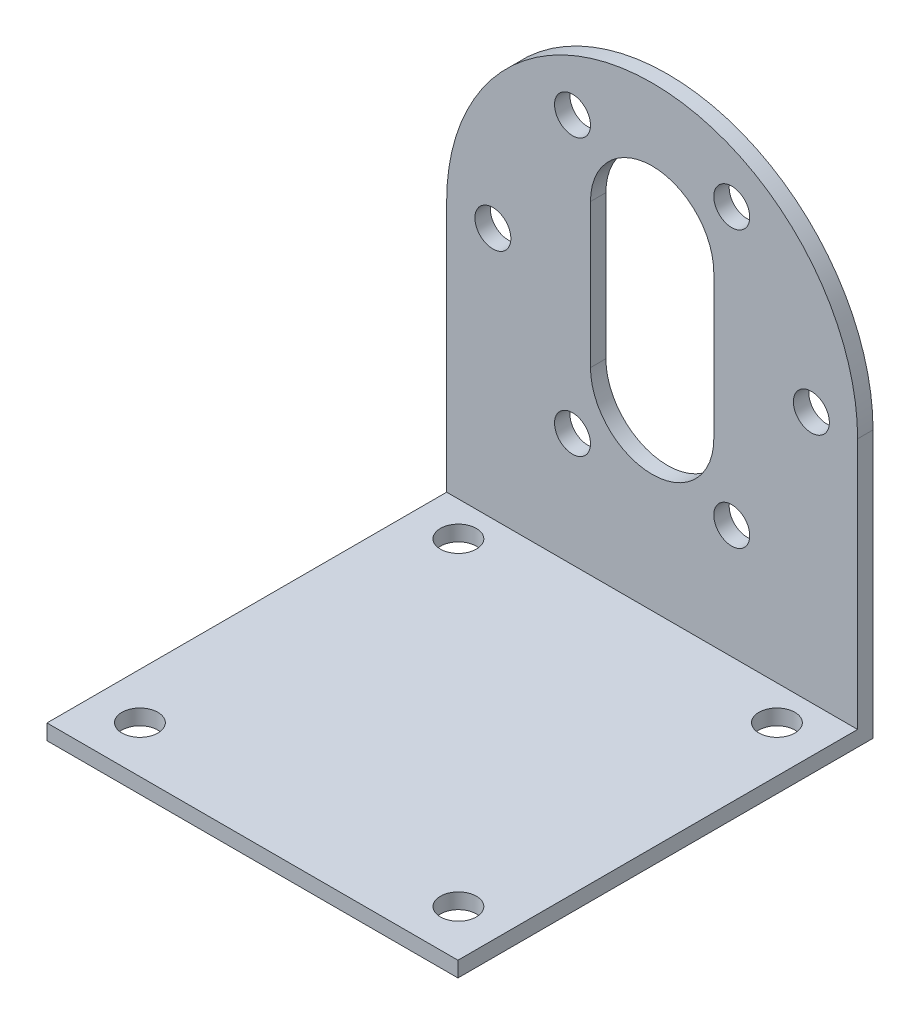
SolidWorks part; units mm, degrees
ref_plane "Front Plane" through (0, 0, 0) normal (0, 0, 1) x (1, 0, 0)
ref_plane "Top Plane" through (0, 0, 0) normal (0, 1, 0) x (1, 0, 0)
ref_plane "Right Plane" through (0, 0, 0) normal (1, 0, 0) x (0, 0, -1)
sketch "Sketch1" plane through (0, 0, 0) normal (0, 0, 1) x (1, 0, 0)
  line L0 (20, 19) -> (20, 33) construction
  line L1 (0, 0) -> (40, 0)
  line L2 (0, 0) -> (0, 26)
  line L3 (0, 26) -> (40, 26)
  line L4 (40, 0) -> (40, 26)
  line L5 (14, 19) -> (14, 33)
  line L6 (26, 19) -> (26, 33)
  arc A0 (0, 26) -> (40, 26) centre (20, 26) cw
  circle A1 centre (35.5, 26) radius 1.75
  arc A2 (14, 19) -> (26, 19) centre (20, 19) ccw
  arc A3 (26, 33) -> (14, 33) centre (20, 33) ccw
  circle A4 centre (27.75, 12.5766) radius 1.75
  circle A5 centre (12.25, 12.5766) radius 1.75
  circle A6 centre (4.5, 26) radius 1.75
  circle A7 centre (12.25, 39.4234) radius 1.75
  circle A8 centre (27.75, 39.4234) radius 1.75
  point P10 (20, 26)
  point P27 (20, 26)
  dimension "D3" = 3.5
  dimension "D4" = 26
  dimension "D1" = 40
  dimension "D2" = 46
  dimension "D5" = 15.5
  dimension "D7" = 12
  dimension "D6" = 6
extrude "Boss-Extrude1" add sketch "Sketch1" along normal blind 1.5 contours A6 L3 L2 L1 L4 A1 L6 A2 L5 A5 A4 | A6 L3 L5 A3 L6 A1 A0 A8 A7
sketch "Sketch2" plane through (0, 0, 0) normal (0, -1, 0) x (1, 0, 0)
  line L0 (40, 1.5) -> (40, 0) construction
  line L1 (0, 0) -> (40, 0)
  line L2 (0, 0) -> (0, 40.4)
  line L3 (0, 40.4) -> (40, 40.4)
  line L4 (40, 0) -> (40, 40.4)
  line L5 (0, 40.4) -> (40, 0) construction
  line L6 (40, 40.4) -> (0, 0) construction
  circle A0 centre (4.5, 35.855) radius 1.75
  circle A1 centre (35.5, 35.855) radius 1.75
  circle A2 centre (35.5, 4.855) radius 1.75
  circle A3 centre (4.5, 4.855) radius 1.75
  dimension "D2" = 3.5
  dimension "D3" = 3.5
  dimension "D4" = 3.5
  dimension "D5" = 3.5
  dimension "D1" = 40.4
  dimension "D6" = 31
  dimension "D7" = 31
extrude "Boss-Extrude2" add sketch "Sketch2" against normal blind 1.5
